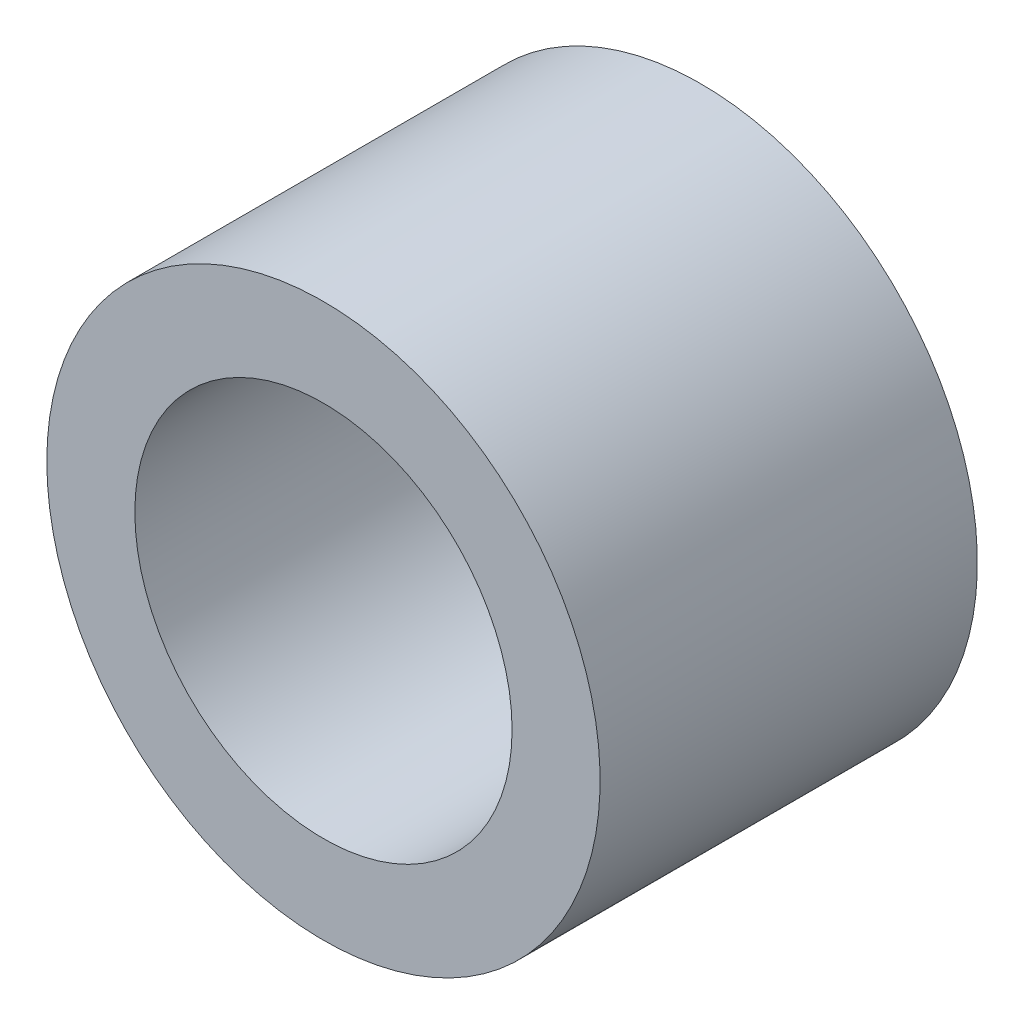
SolidWorks part; units mm, degrees
ref_plane "Front Plane" through (0, 0, 0) normal (0, 0, 1) x (1, 0, 0)
ref_plane "Top Plane" through (0, 0, 0) normal (0, 1, 0) x (1, 0, 0)
ref_plane "Right Plane" through (0, 0, 0) normal (1, 0, 0) x (0, 0, -1)
sketch "Sketch1" plane through (0, 0, 0) normal (0, 0, 1) x (1, 0, 0)
  circle A0 centre (0, 0) radius 3.81
  circle A1 centre (0, 0) radius 5.588
  dimension "D1" = 7.62
  dimension "D2" = 1.778
extrude "Boss-Extrude1" add sketch "Sketch1" along normal blind 7.62
